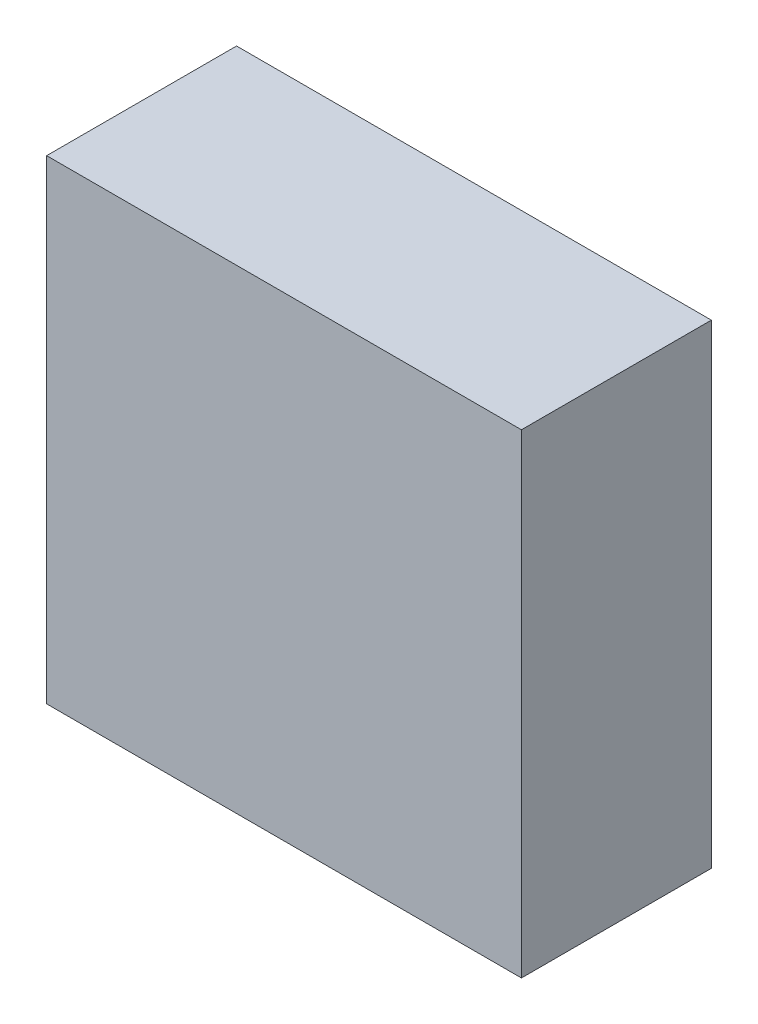
SolidWorks part; units mm, degrees
ref_plane "前视基准面" through (0, 0, 0) normal (0, 0, 1) x (1, 0, 0)
ref_plane "上视基准面" through (0, 0, 0) normal (0, 1, 0) x (1, 0, 0)
ref_plane "右视基准面" through (0, 0, 0) normal (1, 0, 0) x (0, 0, -1)
sketch "草图1" plane through (0, 0, 0) normal (0, 0, 1) x (1, 0, 0)
  line L1 (0, 0) -> (50, 0)
  line L2 (0, 0) -> (0, -50)
  line L3 (0, -50) -> (50, -50)
  line L4 (50, 0) -> (50, -50)
extrude "凸台-拉伸1" add sketch "草图1" along normal blind 20
